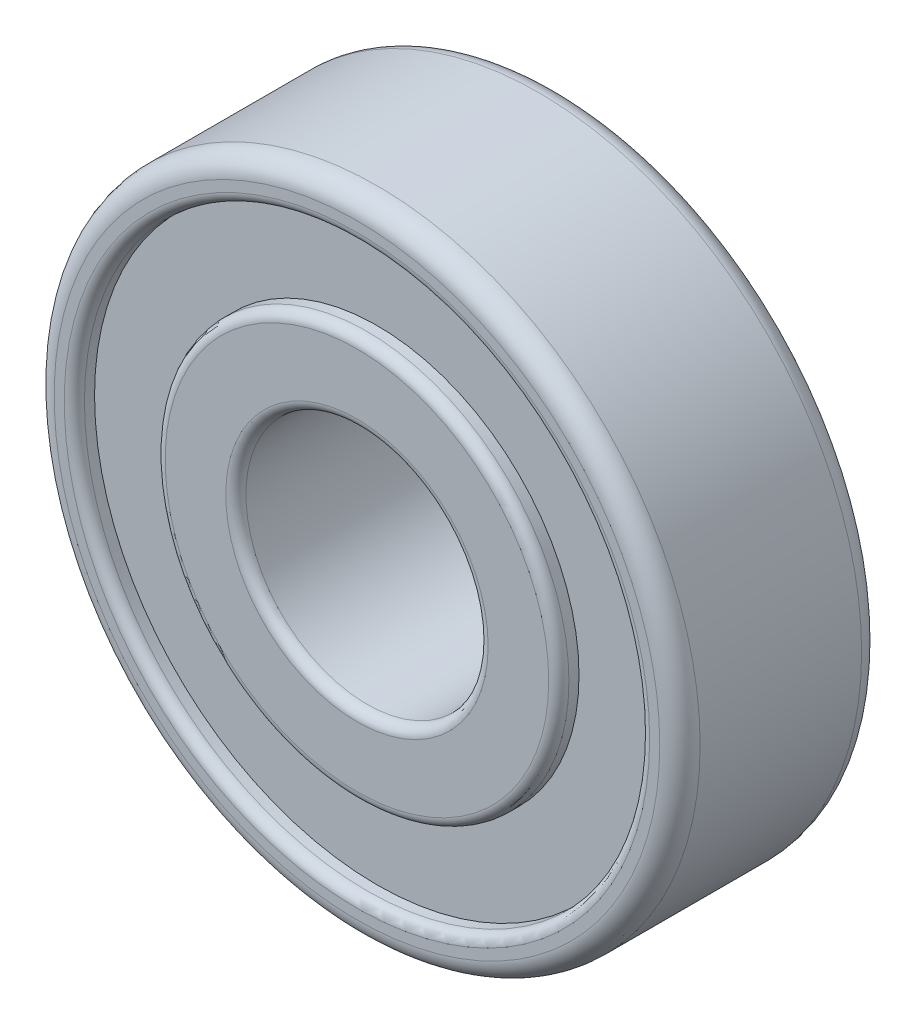
SolidWorks part; units mm, degrees
ref_plane "Plano frontal" through (0, 0, 0) normal (0, 0, 1) x (1, 0, 0)
ref_plane "Plano superior" through (0, 0, 0) normal (0, 1, 0) x (1, 0, 0)
ref_plane "Plano direito" through (0, 0, 0) normal (1, 0, 0) x (0, 0, -1)
sketch "Esboço1" plane through (0, 0, 0) normal (0, 0, 1) x (1, 0, 0)
  circle A0 centre (0, 0) radius 6
  circle A1 centre (0, 0) radius 16
  dimension "D1" = 12
  dimension "D2" = 32
extrude "Ressalto-extrusão1" add sketch "Esboço1" along normal blind 10
sketch "Esboço2" plane through (0, 0, 10) normal (0, 0, 1) x (1, 0, 0)
  circle A0 centre (0, 0) radius 10
  circle A1 centre (0, 0) radius 14
  circle A3 centre (0, 0) radius 16 construction
  circle A4 centre (0, 0) radius 6 construction
  dimension "D1" = 2
  dimension "D2" = 4
extrude "Corte-extrusão1" cut sketch "Esboço2" against normal blind 1
sketch "Esboço3" plane through (0, 0, 0) normal (0, 0, -1) x (-1, 0, 0)
  circle A0 centre (0, 0) radius 9
  circle A1 centre (0, 0) radius 12.5
  circle A2 centre (0, 0) radius 16 construction
  circle A3 centre (0, 0) radius 6 construction
  dimension "D1" = 3.5
  dimension "D2" = 3
extrude "Corte-extrusão2" cut sketch "Esboço3" against normal blind 1
fillet "Fillet1" radius 1 2 edges at (16, 0, 10) (16, 0, 0)
fillet "Fillet2" radius 0.5 6 edges at (6, 0, 0) (6, 0, 10) (-12.5, 0, 0) (14, 0, 10) (10, 0, 10) (-9, 0, 0)
